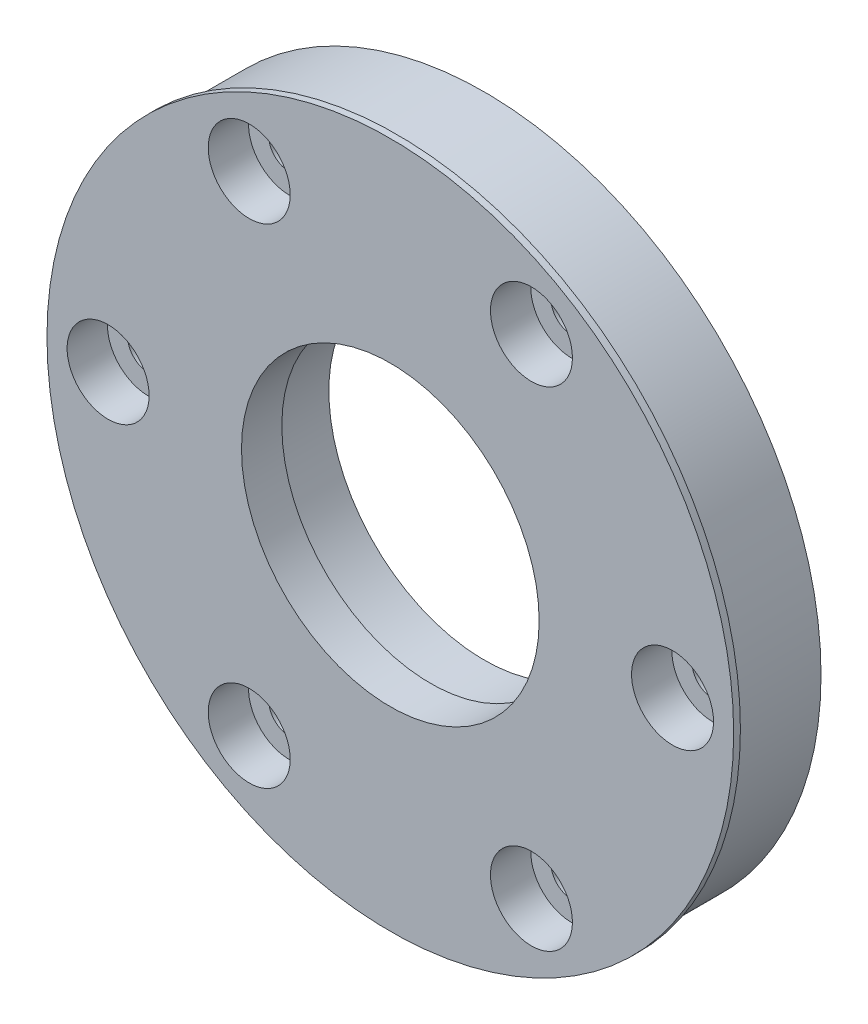
SolidWorks part; units mm, degrees
material "ABS"
ref_plane "Front Plane" through (0, 0, 0) normal (0, 0, 1) x (1, 0, 0)
ref_plane "Top Plane" through (0, 0, 0) normal (0, 1, 0) x (1, 0, 0)
ref_plane "Right Plane" through (0, 0, 0) normal (1, 0, 0) x (0, 0, -1)
sketch "Output Master Sketch" plane through (0, 0, 0) normal (0, 0, 1) x (1, 0, 0)
  circle A0 centre (0, 0) radius 21 construction
  circle A1 centre (21, 0) radius 3.05 construction
  circle A2 centre (10.5, -18.1865) radius 3.05 construction
  circle A3 centre (-10.5, -18.1865) radius 3.05 construction
  circle A4 centre (-21, 0) radius 3.05 construction
  circle A5 centre (-10.5, 18.1865) radius 3.05 construction
  circle A6 centre (10.5, 18.1865) radius 3.05 construction
  circle A7 centre (0, 0) radius 25.05
  point P17 (0, 0)
sketch "Sketch2" plane through (0, 0, 0) normal (0, 0, 1) x (1, 0, 0)
  circle A0 centre (0, 0) radius 25.05
  circle A1 centre (0, 0) radius 25.05 construction
extrude "Boss-Extrude1" add sketch "Sketch2" along normal blind 7
sketch "Sketch3" plane through (0, 0, 7) normal (0, 0, 1) x (1, 0, 0)
  circle A0 centre (-21, 0) radius 3.05
  circle A1 centre (-21, 0) radius 3.05 construction
  circle A2 centre (-10.5, 18.1865) radius 3.05
  circle A3 centre (10.5, 18.1865) radius 3.05
  circle A4 centre (21, 0) radius 3.05
  circle A5 centre (10.5, -18.1865) radius 3.05
  circle A6 centre (-10.5, -18.1865) radius 3.05
  point P18 (0, 0)
  dimension "D1" = 6.1
  dimension "D2" = 6
extrude "Dowel Pin Cutout" cut sketch "Sketch3" against normal blind 3
sketch "Sketch4" plane through (0, 0, 7) normal (0, 0, 1) x (1, 0, 0)
  circle A0 centre (0, 0) radius 25.05
  circle A1 centre (0, 0) radius 25.55
  circle A3 centre (0, 0) radius 25.05 construction
  dimension "D1" = 0.5
extrude "Main Housing Bearing Retainer" add sketch "Sketch4" against normal blind 0.5
sketch "Sketch5" plane through (0, 0, 0) normal (0, 0, -1) x (-1, 0, 0)
  circle A0 centre (-21, 0) radius 1.55
  circle A1 centre (-10.5, 18.1865) radius 1.55
  circle A2 centre (10.5, 18.1865) radius 1.55
  circle A3 centre (21, 0) radius 1.55
  circle A4 centre (10.5, -18.1865) radius 1.55
  circle A5 centre (-10.5, -18.1865) radius 1.55
  point P15 (0, 0)
  dimension "D1" = 3.1
  dimension "D2" = 6
extrude "M3 Thru" cut sketch "Sketch5" against normal through all
sketch "Sketch6" plane through (0, 0, 0) normal (0, 0, -1) x (-1, 0, 0)
  circle A0 centre (-21, 0) radius 3
  circle A1 centre (-10.5, 18.1865) radius 3
  circle A2 centre (10.5, 18.1865) radius 3
  circle A3 centre (21, 0) radius 3
  circle A4 centre (10.5, -18.1865) radius 3
  circle A5 centre (-10.5, -18.1865) radius 3
  point P15 (0, 0)
  dimension "D1" = 6
  dimension "D2" = 6
extrude "M3 Button Head Cutout" cut sketch "Sketch6" against normal blind 1.7
sketch "Sketch8" plane through (0, 0, 7) normal (0, 0, 1) x (1, 0, 0)
  circle A0 centre (0, 0) radius 11.575
  dimension "D1" = 23.15
extrude "Input Shaft Bearing Cutout" cut sketch "Sketch8" against normal through all
sketch "Sketch9" plane through (0, 0, 0) normal (0, 0, -1) x (-1, 0, 0)
  circle A0 centre (0, 0) radius 11.575
  circle A1 centre (0, 0) radius 11.075
  circle A2 centre (0, 0) radius 11.575 construction
  dimension "D1" = 0.5
extrude "Input Shaft Bearing Retainer" add sketch "Sketch9" along normal blind 3 from surface at -7 starting at face at (11.575, 0, 7)
